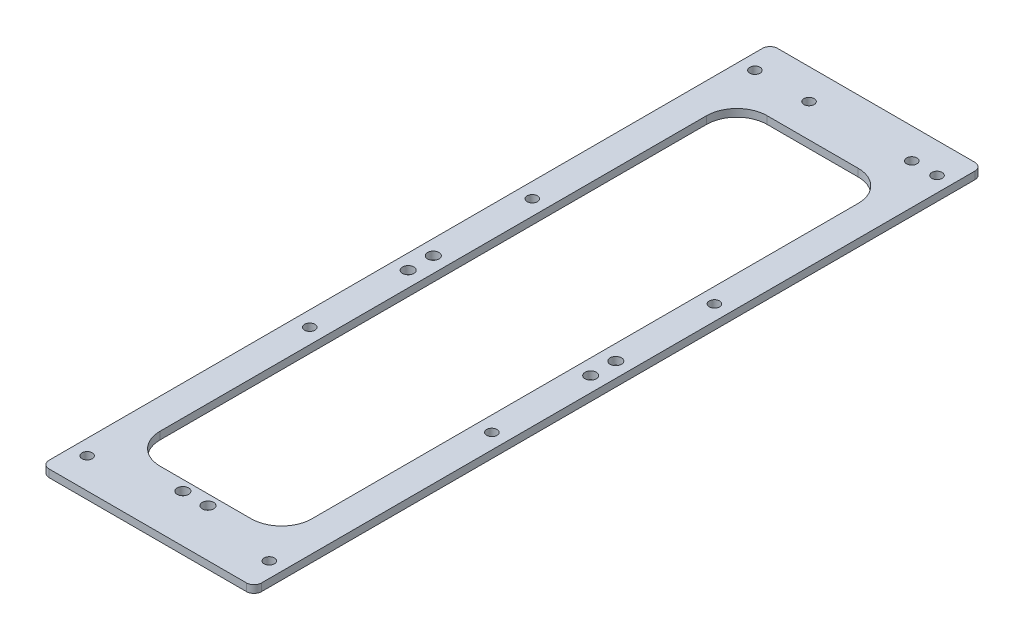
SolidWorks part; units mm, degrees
ref_plane "Front Plane" through (0, 0, 0) normal (0, 0, 1) x (1, 0, 0)
ref_plane "Top Plane" through (0, 0, 0) normal (0, 1, 0) x (1, 0, 0)
ref_plane "Right Plane" through (0, 0, 0) normal (1, 0, 0) x (0, 0, -1)
sketch "Sketch1" plane through (0, 0, 0) normal (0, 1, 0) x (1, 0, 0)
  line L1 (-44.45, 152.4) -> (44.45, 152.4)
  line L2 (-44.45, 152.4) -> (-44.45, -152.4)
  line L3 (-44.45, -152.4) -> (44.45, -152.4)
  line L4 (44.45, 152.4) -> (44.45, -152.4)
  line L14 (0, 0) -> (0, 187.5455) construction
  line L21 (0, 0) -> (44.45, 0) construction
  line L37 (-31.75, 125.8231) -> (31.75, 125.8231)
  line L40 (-31.75, 125.8231) -> (-31.75, -128.1769)
  line L43 (-31.75, -128.1769) -> (31.75, -128.1769)
  line L46 (31.75, 125.8231) -> (31.75, -128.1769)
  point P4 (0, 152.4)
  point P6 (-44.45, 0)
  dimension "D4" = 254
  dimension "D2" = 88.9
  dimension "D3" = 304.8
  dimension "D6" = 12.7
  dimension "D12" = 12.7
extrude "Boss-Extrude1" add sketch "Sketch1" along normal blind 3.175
sketch "Sketch7" plane through (0, 3.175, 0) normal (0, 1, 0) x (1, 0, 0)
  line L1 (-44.45, 152.4) -> (-44.45, -152.4) construction
  line L2 (0, 0) -> (0, 246.0772) construction
  line L3 (0, 0) -> (301.4392, 0) construction
  line L4 (44.45, 152.4) -> (-44.45, 152.4) construction
  circle A0 centre (-38.1, 139.7363) radius 2.159
  circle A10 centre (38.1, 139.7363) radius 2.159
  circle A13 centre (-38.1, 46.6029) radius 2.159
  circle A14 centre (-38.1, -46.5305) radius 2.159
  circle A15 centre (-38.1, -139.664) radius 2.159
  circle A16 centre (38.1, 46.6021) radius 2.159
  circle A17 centre (38.1, -46.5321) radius 2.159
  circle A18 centre (38.1, -139.6662) radius 2.159
  dimension "D1" = 4.318
  dimension "D3" = 6.35
  dimension "D4" = 4
  dimension "D5" = 4
  dimension "D8" = 12.6637
extrude "Cut-Extrude2" cut sketch "Sketch7" against normal through all
fillet "Fillet1" radius 12.7 4 edges at (31.75, 1.5875, 128.1769) (-31.75, 1.5875, 128.1769) (-31.75, 1.5875, -125.8231) (31.75, 1.5875, -125.8231)
sketch "Sketch8" [suppressed] plane through (0, 3.175, 0) normal (0, 1, 0) x (1, 0, 0)
  line L0 (184.15, 139.7) -> (-184.15, 139.7) construction
  line L1 (0, 139.7) -> (0, 110.7046) construction
  circle A0 centre (-15.7442, 133.35) radius 2.159
  circle A1 centre (15.7442, 133.35) radius 2.159
  dimension "D5" = 4.318
  dimension "D6" = 4.318
  dimension "D1" = 6.35
  dimension "D2" = 6.35
  dimension "D3" = 31.4884
  dimension "D4" = 15.7442
fillet "Fillet3" radius 3.175 4 edges at (-44.45, 1.5875, 152.4) (44.45, 1.5875, 152.4) (44.45, 1.5875, -152.4) (-44.45, 1.5875, -152.4)
sketch "Sketch9" plane through (0, 3.175, 0) normal (0, 1, 0) x (1, 0, 0)
  line L1 (44.45, -149.225) -> (44.45, 149.225) construction
  line L2 (41.275, 152.4) -> (-41.275, 152.4) construction
  circle A0 centre (-15.4178, 139.7) radius 2.159
  circle A1 centre (27.5844, 139.7) radius 2.159
  dimension "D1" = 4.318
  dimension "D2" = 4.318
  dimension "D5" = 12.7
  dimension "D6" = 12.7
  dimension "D3" = 59.8678
  dimension "D4" = 16.8656
extrude "Cut-Extrude4" cut sketch "Sketch9" against normal through all contours A0 | A1
sketch "Sketch10" plane through (0, 3.175, 0) normal (0, 1, 0) x (1, 0, 0)
  line L0 (0, 0) -> (0, -287.9287) construction
  line L1 (-19.05, -128.1769) -> (19.05, -128.1769) construction
  circle A0 centre (-5.2462, -132.4582) radius 2.3812
  circle A2 centre (5.2462, -132.4582) radius 2.3813
  point P5 (0, 0)
  dimension "D1" = 10.4925
  dimension "D2" = 4.2813
extrude "Sonar Holes" cut sketch "Sketch10" against normal through all
sketch "Sketch11" plane through (0, 3.175, 0) normal (0, 1, 0) x (1, 0, 0)
  line L0 (0, 0) -> (-173.0616, 0) construction
  line L1 (0, 0) -> (0, -174.5172) construction
  circle A0 centre (-38.1811, 5.2462) radius 2.3812
  circle A1 centre (-38.1811, -5.2463) radius 2.3812
  circle A2 centre (38.1811, -5.2463) radius 2.3812
  circle A3 centre (38.1811, 5.2462) radius 2.3812
  dimension "D1" = 10.4925
extrude "Sonar Holes 2: Electric Boogaloo" cut sketch "Sketch11" against normal through all
